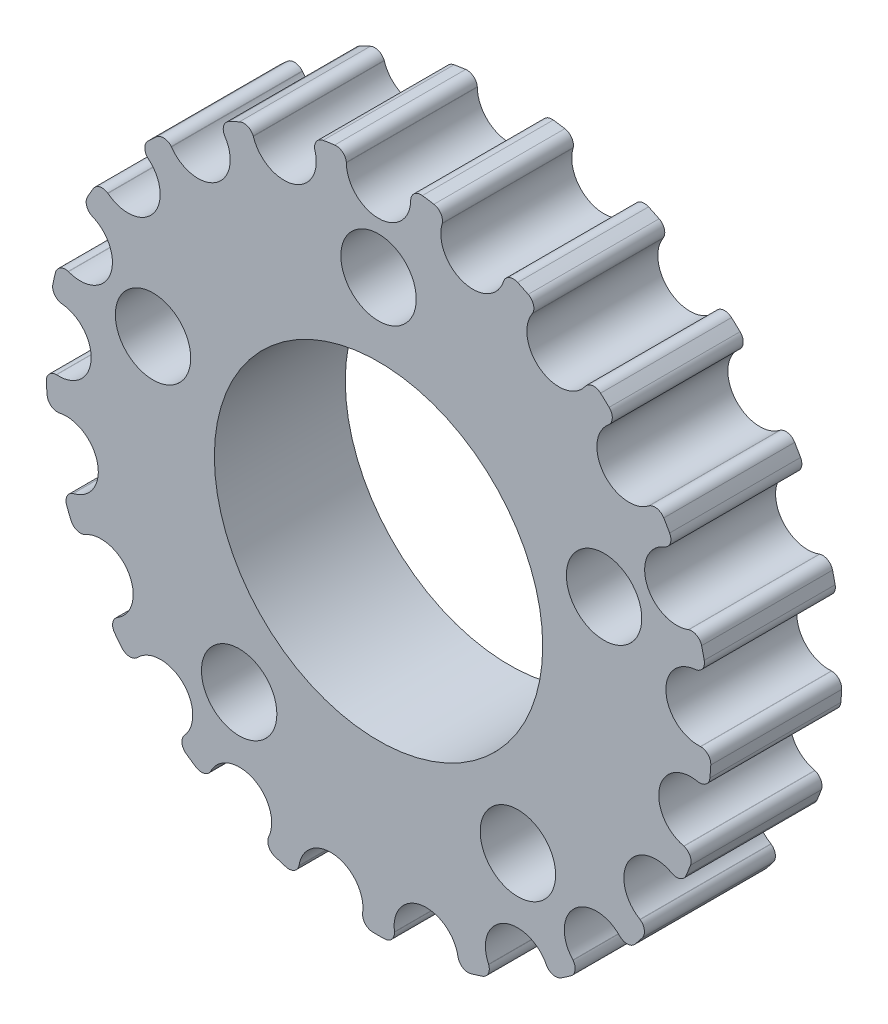
SolidWorks part; units mm, degrees
ref_plane "Front Plane" through (0, 0, 0) normal (0, 0, 1) x (1, 0, 0)
ref_plane "Top Plane" through (0, 0, 0) normal (0, 1, 0) x (1, 0, 0)
ref_plane "Right Plane" through (0, 0, 0) normal (1, 0, 0) x (0, 0, -1)
sketch "Pitch diameter" plane through (0, 0, 0) normal (0, 0, 1) x (1, 0, 0)
  circle A0 centre (0, 0) radius 16.7113 construction
  dimension "D1" = 33.4225
sketch "Sketch2" plane through (0, 0, 0) normal (0, 0, 1) x (1, 0, 0)
  circle A0 centre (0, 0) radius 16.1398
  dimension "D1" = 32.2795
extrude "Boss-Extrude1" add sketch "Sketch2" along normal blind 6.35
sketch "Sketch3" plane through (0, 0, 0) normal (0, 0, -1) x (-1, 0, 0)
  line L0 (-1.6121, 16.0591) -> (-1.56, 15.5398)
  line L1 (1.6121, 16.0591) -> (1.56, 15.5398)
  line L2 (-1.56, 15.5398) -> (1.56, 15.5398) construction
  circle A0 centre (0, 0) radius 16.1398 construction
  arc A1 (-1.56, 15.5398) -> (1.56, 15.5398) centre (0, 15.5398) ccw
  circle A2 centre (0, 0) radius 16.1398 construction
  arc A3 (1.6121, 16.0591) -> (-1.6121, 16.0591) centre (0, 0) ccw
  point P10 (0, 15.5398)
  point P15 (0, 13.9798)
  point P16 (0, 16.1398)
  dimension "D1" = 1.56
  dimension "D2" = 2.16
extrude "Cut-Extrude1" cut sketch "Sketch3" against normal through all
fillet "Fillet1" radius 0.5 2 edges at (-1.6121, 16.0591, 3.175) (1.6121, 16.0591, 3.175)
pattern_circular "CirPattern1" count 21 over 360 about axis through (0, 0, 0) along (0, 0, 1) of "Cut-Extrude1", "Fillet1"
sketch "Sketch4" plane through (0, 0, 6.35) normal (0, 0, 1) x (1, 0, 0)
  circle A0 centre (0, 0) radius 7.9629
  dimension "D1" = 15.9258
extrude "Cut-Extrude2" cut sketch "Sketch4" against normal through all
sketch "Sketch5" plane through (0, 0, 6.35) normal (0, 0, 1) x (1, 0, 0)
  line L0 (0, 0) -> (0, 11.5)
  point P0 (0, 0)
  point P7 (0, 0)
  dimension "D1" = 11.5
sketch "Sketch9" plane through (0, 0, 6.35) normal (0, 0, 1) x (1, 0, 0)
  point P0 (0, 11.5)
hole_wizard "#6 Clearance Hole1" positions "Sketch9" profile "Sketch10" hole size "#6" standard "ANSI Inch" end condition through all
sketch "Sketch10" plane through (0, 11.5, 6.35) normal (1, 0, 0) x (0, -1, 0)
  line L0 (0, 0) -> (0, 6.35)
  line L1 (0, 6.35) -> (1.8288, 6.35)
  line L2 (1.8288, 6.35) -> (1.8288, 0)
  line L5 (1.8288, 0) -> (0, 0)
  line L11 (0, -6.35) -> (0, 107.95) construction
  dimension "Thru Hole Dia." = 3.6576
  dimension "Thru Hole Depth" = 6.35
pattern_circular "CirPattern2" count 5 over 360 about axis through (0, 0, 0) along (0, 0, 1) of "#6 Clearance Hole1"
equation "\"NumberOfTeeth\" = 21"
equation "\"Pitch\"= 5mm"
equation "\"PitchDiameter\"= ( \"Pitch\" * \"NumberOfTeeth\" ) / Pi"
equation "\"OD\"= \"PitchDiameter\" - 0.0225in * 2"
equation "\"D1@Pitch diameter\" = \"PitchDiameter\""
equation "\"D1@Sketch2\"=\"OD\""
equation "\"D1@CirPattern1\"=\"NumberOfTeeth\""
